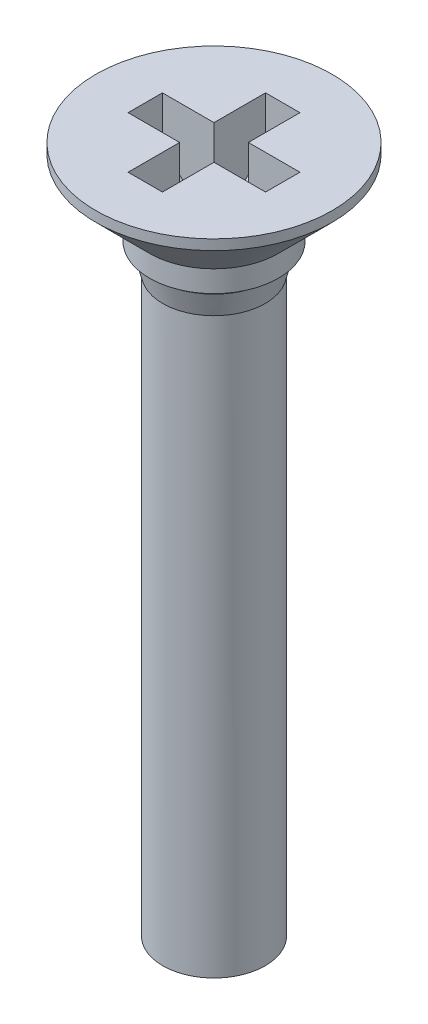
SolidWorks part; units mm, degrees
ref_plane "Vorderseite" through (0, 0, 0) normal (0, 0, 1) x (1, 0, 0)
ref_plane "Oben" through (0, 0, 0) normal (0, 1, 0) x (1, 0, 0)
ref_plane "Rechts" through (0, 0, 0) normal (1, 0, 0) x (0, 0, -1)
sketch "Skizze1" plane through (0, 0, 0) normal (0, 0, 1) x (1, 0, 0)
  line L0 (0, 0) -> (2.75, 0)
  line L1 (2.75, 0) -> (2.75, -0.2375)
  line L2 (2.75, -0.2375) -> (1.5, -1.4875)
  line L3 (1.3375, -1.9875) -> (1.3375, -2.1126)
  line L4 (1.3375, -2.1126) -> (1.1935, -2.65)
  line L5 (1.1935, -2.65) -> (1.1935, -8)
  line L6 (1.1935, -8) -> (0, -8)
  line L7 (0, 0) -> (0, -8) construction
  line L8 (0, 0) -> (0, -8)
  line L10 (1.5, -1.4875) -> (1.5, -1.9875)
  line L12 (1.5, -1.9875) -> (1.3375, -1.9875)
  point P3 (1.3375, -1.65)
  dimension "D1" = 45
  dimension "D2" = 15
  dimension "K" = 1.65
  dimension "DA" = 5.5
  dimension "DK" = 2.387
  dimension "L" = 8
  dimension "DG" = 3
  dimension "A" = 1
  dimension "DF" = 2.675
  dimension "P" = 0.5
revolve "Basis-Rotation" add sketch "Skizze1" angle 360 about L7
sketch "Skizze2" plane through (0, 0, 0) normal (0, 0, 1) x (1, 0, 0)
  line L0 (0, -2.1) -> (0, 0) construction
  line L1 (0, 0) -> (0, -8) construction
  line L2 (-0.55, -2.1) -> (0.55, -2.1)
  line L3 (1.6, 0) -> (1.6, -1.05)
  line L4 (1.6, -1.05) -> (0.55, -2.1)
  line L5 (1.6, 0) -> (-1.6, 0)
  line L6 (-1.6, -1.05) -> (-0.55, -2.1)
  line L7 (-1.6, 0) -> (-1.6, -1.05)
  line L8 (0, -1.05) -> (1.6, -1.05) construction
  line L9 (2.75, 0) -> (-2.75, 0) construction
  line L11 (1.5, -1.4875) -> (2.75, -0.2375) construction
  point P11 (0, 0)
  dimension "M" = 3.2
  dimension "T" = 2.1
extrude "Kreuzschlitz1 H" cut sketch "Skizze2" against normal blind 0.4 and the other way blind 0.4
sketch "Skizze3" plane through (0, 0, 0) normal (1, 0, 0) x (0, 0, -1)
  line L0 (0, -2.1) -> (0, 0) construction
  line L2 (-0.55, -2.1) -> (0.55, -2.1)
  line L3 (1.6, 0) -> (1.6, -1.05)
  line L4 (1.6, -1.05) -> (0.55, -2.1)
  line L5 (1.6, 0) -> (-1.6, 0)
  line L6 (-1.6, -1.05) -> (-0.55, -2.1)
  line L7 (-1.6, 0) -> (-1.6, -1.05)
  line L8 (0, -1.05) -> (1.6, -1.05) construction
  point P11 (0, 0)
extrude "Kreuzschlitz2 H" cut sketch "Skizze3" against normal blind 0.4 and the other way blind 0.4
sketch "Skizze4" plane through (2.4522, 0, -1.8507) normal (0, 1, 0) x (-1, 0, 0)
  line L0 (7.3522, 1.8507) -> (-2.4478, 1.8507) construction
  line L1 (2.4522, -3.0493) -> (2.4522, 6.7507) construction
  line L2 (-2.4478, 1.0342) -> (-2.4478, 2.6672)
  line L3 (-2.4478, 1.0342) -> (0.0059, 1.0342)
  line L4 (0.0059, 1.0342) -> (0.8191, 0.6258)
  line L5 (1.2273, 0.2176) -> (-1.0126, -1.6141)
  line L6 (0.8191, 0.6258) -> (-1.0126, -1.6141)
  line L7 (1.6357, -0.5956) -> (1.2273, 0.2176)
  line L8 (1.6357, -3.0493) -> (1.6357, -0.5956)
  line L9 (1.6357, -3.0493) -> (3.2687, -3.0493)
  line L10 (3.2687, -3.0493) -> (3.2687, -0.5956)
  line L11 (3.2687, -0.5956) -> (3.6772, 0.2176)
  line L12 (2.4522, 1.8507) -> (-1.0126, -1.6141) construction
  line L13 (4.0854, 0.6258) -> (5.917, -1.6141)
  line L14 (3.6772, 0.2176) -> (5.917, -1.6141)
  line L15 (4.8986, 1.0342) -> (4.0854, 0.6258)
  line L16 (7.3522, 1.0342) -> (4.8986, 1.0342)
  line L17 (7.3522, 1.0342) -> (7.3522, 2.6672)
  line L18 (7.3522, 2.6672) -> (4.8986, 2.6672)
  line L19 (4.8986, 2.6672) -> (4.0854, 3.0757)
  line L20 (3.6772, 3.4839) -> (5.917, 5.3156)
  line L21 (4.0854, 3.0757) -> (5.917, 5.3156)
  line L22 (3.2687, 4.2971) -> (3.6772, 3.4839)
  line L23 (3.2687, 6.7507) -> (3.2687, 4.2971)
  line L24 (1.6357, 6.7507) -> (3.2687, 6.7507)
  line L25 (1.6357, 6.7507) -> (1.6357, 4.2971)
  line L26 (1.6357, 4.2971) -> (1.2273, 3.4839)
  line L27 (0.8191, 3.0757) -> (-1.0126, 5.3156)
  line L28 (1.2273, 3.4839) -> (-1.0126, 5.3156)
  line L29 (0.0059, 2.6672) -> (0.8191, 3.0757)
  line L30 (-2.4478, 2.6672) -> (0.0059, 2.6672)
  circle A0 centre (2.4522, 1.8507) radius 4.9 construction
  circle A1 centre (2.4522, 1.8507) radius 2.0415 construction
  circle A2 centre (2.4522, 1.8507) radius 2.579 construction
  dimension "X2" = 4.083
  dimension "X1" = 5.158
  dimension "M" = 9.8
  dimension "D3" = 5.725
  dimension "X3" = 1.633
sketch "Sketch1" plane through (0, -8, 0) normal (0, -1, 0) x (1, 0, 0)
  circle A0 centre (0, 0) radius 1.1935
extrude "Boss-Extrude1" add sketch "Sketch1" along normal blind 8
